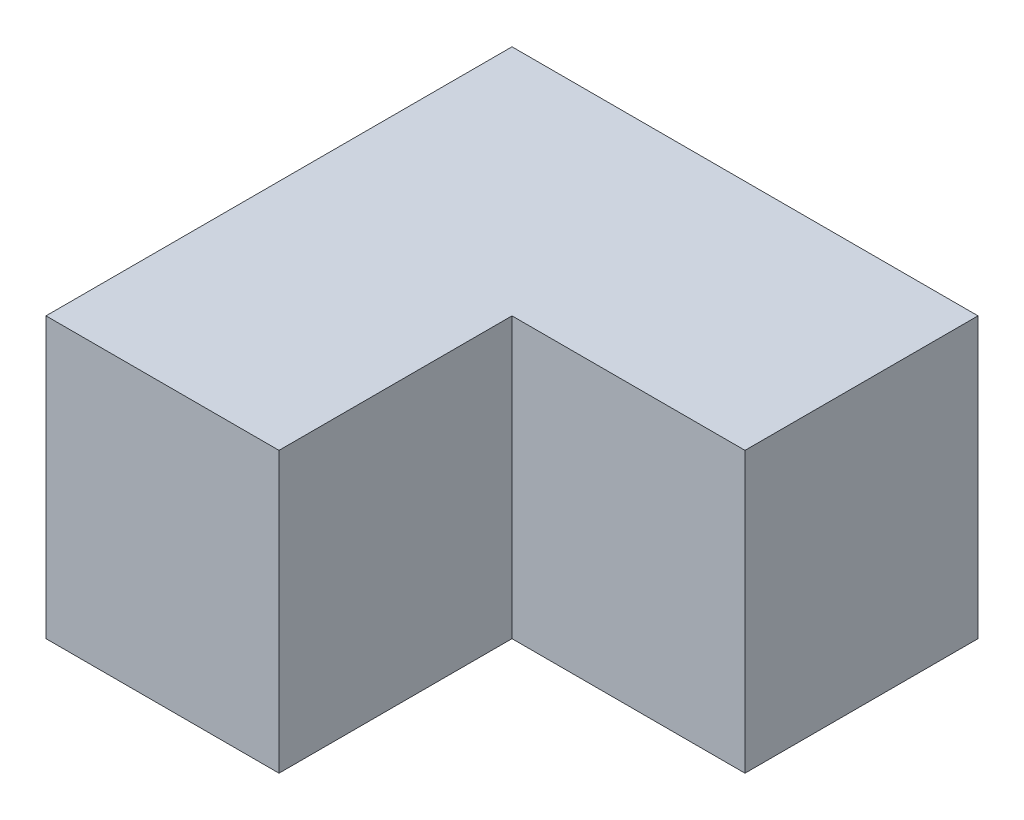
SolidWorks part; units mm, degrees
ref_plane "Front Plane" through (0, 0, 0) normal (0, 0, 1) x (1, 0, 0)
ref_plane "Top Plane" through (0, 0, 0) normal (0, 1, 0) x (1, 0, 0)
ref_plane "Right Plane" through (0, 0, 0) normal (1, 0, 0) x (0, 0, -1)
sketch "Sketch1" plane through (0, 0, 0) normal (0, 1, 0) x (1, 0, 0)
  line L1 (-15, -15) -> (15, -15)
  line L2 (-15, -15) -> (-15, 15)
  line L3 (-15, 15) -> (15, 15)
  line L4 (15, -15) -> (15, 15)
  line L5 (-15, -15) -> (15, 15) construction
  line L6 (-15, 15) -> (15, -15) construction
  point P0 (0, 0)
  dimension "D1" = 30
  dimension "D2" = 30
extrude "Boss-Extrude1" add sketch "Sketch1" along normal blind 18
sketch "Sketch2" plane through (0, 18, 0) normal (0, 1, 0) x (1, 0, 0)
  line L1 (15, -15) -> (0, -15)
  line L2 (15, -15) -> (15, 0)
  line L3 (15, 0) -> (0, 0)
  line L4 (0, -15) -> (0, 0)
extrude "Cut-Extrude1" cut sketch "Sketch2" against normal through all
